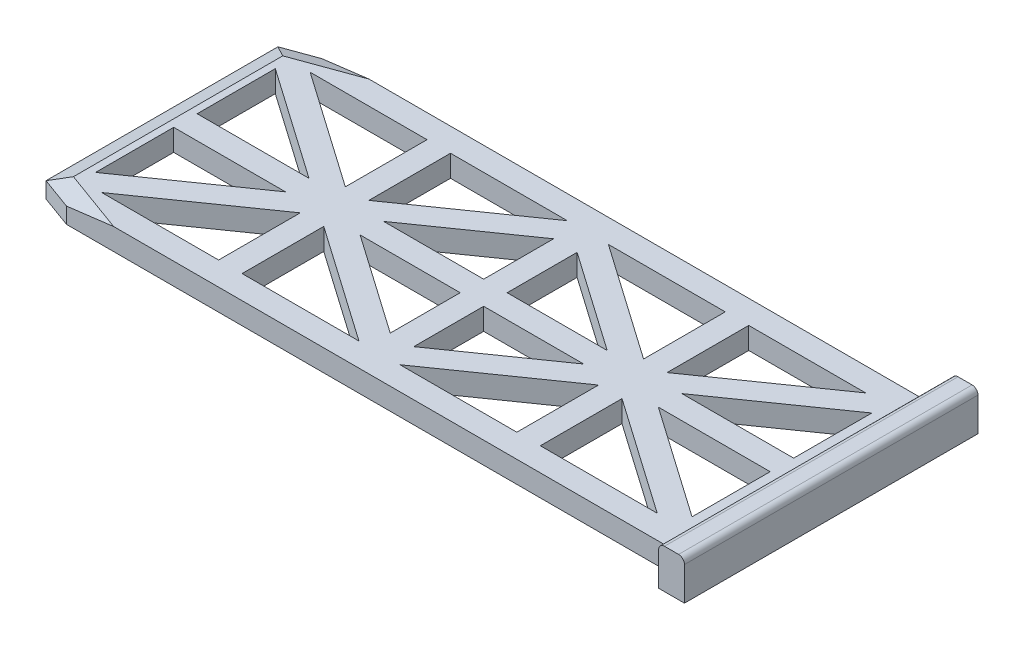
SolidWorks part; units mm, degrees
ref_plane "Front" through (0, 0, 0) normal (0, 0, 1) x (1, 0, 0)
ref_plane "Top" through (0, 0, 0) normal (0, 1, 0) x (1, 0, 0)
ref_plane "Right" through (0, 0, 0) normal (1, 0, 0) x (0, 0, -1)
sketch "Sketch1" plane through (0, 0, 0) normal (0, 1, 0) x (1, 0, 0)
  line L1 (0, 0) -> (114, 0)
  line L2 (0, 0) -> (0, 43.5)
  line L3 (0, 43.5) -> (114, 43.5)
  line L4 (114, 0) -> (114, 43.5)
  dimension "D1" = 114
  dimension "D2" = 43.5
extrude "Boss-Extrude1" add sketch "Sketch1" along normal blind 3.7
sketch "Sketch2" plane through (0, 3.7, 0) normal (0, 1, 0) x (1, 0, 0)
  line L0 (0, 0) -> (114, 0) construction
  line L1 (114, 43.5) -> (109.6, 43.5)
  line L2 (114, 43.5) -> (114, 0)
  line L3 (114, 0) -> (109.6, 0)
  line L4 (109.6, 43.5) -> (109.6, 0)
  dimension "D1" = 4.4
extrude "Boss-Extrude2" add sketch "Sketch2" along normal blind 3
chamfer "Chamfer1" distance 2 angle 70 2 edges at (0, 1.85, -43.5) (0, 1.85, 0)
sketch "Sketch3" plane through (0, 3.7, 0) normal (0, 1, 0) x (1, 0, 0)
  line L0 (52.8, 39.5) -> (52.8, 4)
  line L5 (52.8, 39.5) -> (56.8, 39.5)
  line L6 (52.8, 4) -> (56.8, 4)
  line L7 (56.8, 39.5) -> (56.8, 4)
  line L8 (109.6, 43.5) -> (5.495, 43.5) construction
  line L9 (4, 4) -> (105.6, 4)
  line L14 (4, 4) -> (4, 39.5)
  line L15 (4, 39.5) -> (105.6, 39.5)
  line L20 (105.6, 4) -> (105.6, 39.5)
  line L21 (0, 41.5) -> (0, 2) construction
  line L26 (5.495, 0) -> (109.6, 0) construction
  line L27 (109.6, 43.5) -> (109.6, 0) construction
  line L32 (54.8, 39.5) -> (54.8, 4) construction
  line L33 (4, 21.75) -> (105.6, 21.75) construction
  line L34 (4, 19.75) -> (105.6, 19.75)
  line L35 (4, 19.75) -> (4, 23.75)
  line L36 (105.6, 19.75) -> (105.6, 23.75)
  line L37 (4, 23.75) -> (105.6, 23.75)
  line L38 (4, 19.75) -> (105.6, 23.75) construction
  line L39 (105.6, 19.75) -> (4, 23.75) construction
  line L40 (4, 4) -> (54.8, 39.5) construction
  line L41 (4, 39.5) -> (54.8, 4) construction
  line L42 (54.8, 39.5) -> (105.6, 4) construction
  line L43 (54.8, 4) -> (105.6, 39.5) construction
  line L44 (5.1456, 2.3606) -> (55.9456, 37.8606)
  line L45 (5.1456, 2.3606) -> (2.8544, 5.6394)
  line L46 (55.9456, 37.8606) -> (53.6544, 41.1394)
  line L47 (2.8544, 5.6394) -> (53.6544, 41.1394)
  line L48 (5.1456, 2.3606) -> (53.6544, 41.1394) construction
  line L49 (55.9456, 37.8606) -> (2.8544, 5.6394) construction
  line L50 (53.6544, 2.3606) -> (2.8544, 37.8606)
  line L51 (53.6544, 2.3606) -> (55.9456, 5.6394)
  line L52 (2.8544, 37.8606) -> (5.1456, 41.1394)
  line L53 (55.9456, 5.6394) -> (5.1456, 41.1394)
  line L54 (53.6544, 2.3606) -> (5.1456, 41.1394) construction
  line L55 (2.8544, 37.8606) -> (55.9456, 5.6394) construction
  line L56 (104.4544, 2.3606) -> (53.6544, 37.8606)
  line L57 (104.4544, 2.3606) -> (106.7456, 5.6394)
  line L58 (53.6544, 37.8606) -> (55.9456, 41.1394)
  line L59 (106.7456, 5.6394) -> (55.9456, 41.1394)
  line L60 (104.4544, 2.3606) -> (55.9456, 41.1394) construction
  line L61 (53.6544, 37.8606) -> (106.7456, 5.6394) construction
  line L62 (55.9456, 2.3606) -> (106.7456, 37.8606)
  line L63 (55.9456, 2.3606) -> (53.6544, 5.6394)
  line L64 (106.7456, 37.8606) -> (104.4544, 41.1394)
  line L65 (53.6544, 5.6394) -> (104.4544, 41.1394)
  line L66 (55.9456, 2.3606) -> (104.4544, 41.1394) construction
  line L67 (106.7456, 37.8606) -> (53.6544, 5.6394) construction
  line L68 (27.4, 4) -> (27.4, 39.5)
  line L69 (27.4, 4) -> (31.4, 4)
  line L70 (27.4, 39.5) -> (31.4, 39.5)
  line L71 (31.4, 4) -> (31.4, 39.5)
  line L72 (27.4, 4) -> (31.4, 39.5) construction
  line L73 (27.4, 39.5) -> (31.4, 4) construction
  line L74 (52.8, 39.5) -> (56.8, 4) construction
  line L75 (52.8, 4) -> (56.8, 39.5) construction
  line L76 (78.2, 4) -> (78.2, 39.5)
  line L77 (78.2, 4) -> (82.2, 4)
  line L78 (78.2, 39.5) -> (82.2, 39.5)
  line L79 (82.2, 4) -> (82.2, 39.5)
  line L80 (78.2, 4) -> (82.2, 39.5) construction
  line L81 (78.2, 39.5) -> (82.2, 4) construction
  point P16 (80.2, 21.75)
  point P17 (54.8, 21.75)
  point P18 (29.4, 21.75)
  point P23 (80.2, 21.75)
  point P28 (29.4, 21.75)
  point P29 (80.2, 21.75)
  point P34 (29.4, 21.75)
  point P43 (54.8, 21.75)
  point P44 (83.2952, 4)
  point P54 (80.2, 21.75)
  dimension "D1" = 4
  dimension "D2" = 4
  dimension "D3" = 4
  dimension "D4" = 4
  dimension "D5" = 4
  dimension "D6" = 4
  dimension "D7" = 4
  dimension "D8" = 4
  dimension "D9" = 4
  dimension "D10" = 4
  dimension "D11" = 4
  dimension "D12" = 4
extrude "Cut-Extrude1" cut sketch "Sketch3" against normal blind 7.5 contours L14 L47 L34 | L9 L68 L44 | L37 L50 L14 | L53 L68 L15 | L71 L47 L15 | L44 L37 L0 | L53 L0 L34 | L71 L9 L50 | L7 L65 L34 | L9 L76 L62 | L37 L56 L7 | L59 L76 L15 | L79 L65 L15 | L62 L37 L20 | L59 L20 L34 | L79 L9 L56
sketch "Sketch6" plane through (0, 0, 0) normal (0, 0, 1) x (1, 0, 0)
  line L0 (5.495, 0) -> (114, 0) construction
  line L1 (114, 6.7) -> (109.6, 6.7)
  line L2 (114, 6.7) -> (114, 0)
  line L3 (114, 0) -> (109.6, 0)
  line L4 (109.6, 6.7) -> (109.6, 0)
  line L5 (109.6, 6.7) -> (109.6, 3.7) construction
extrude "Boss-Extrude3" add sketch "Sketch6" along normal blind 3.25 and the other way blind 46.75
fillet "Fillet2" radius 1 2 edges at (114, 6.7, -21.75) (109.6, 6.7, -21.75)
chamfer "Chamfer2" distance 1 angle 70 3 edges at (2.7475, 3.7, -42.5) (2.7475, 3.7, -1) (0, 3.7, -21.75)
